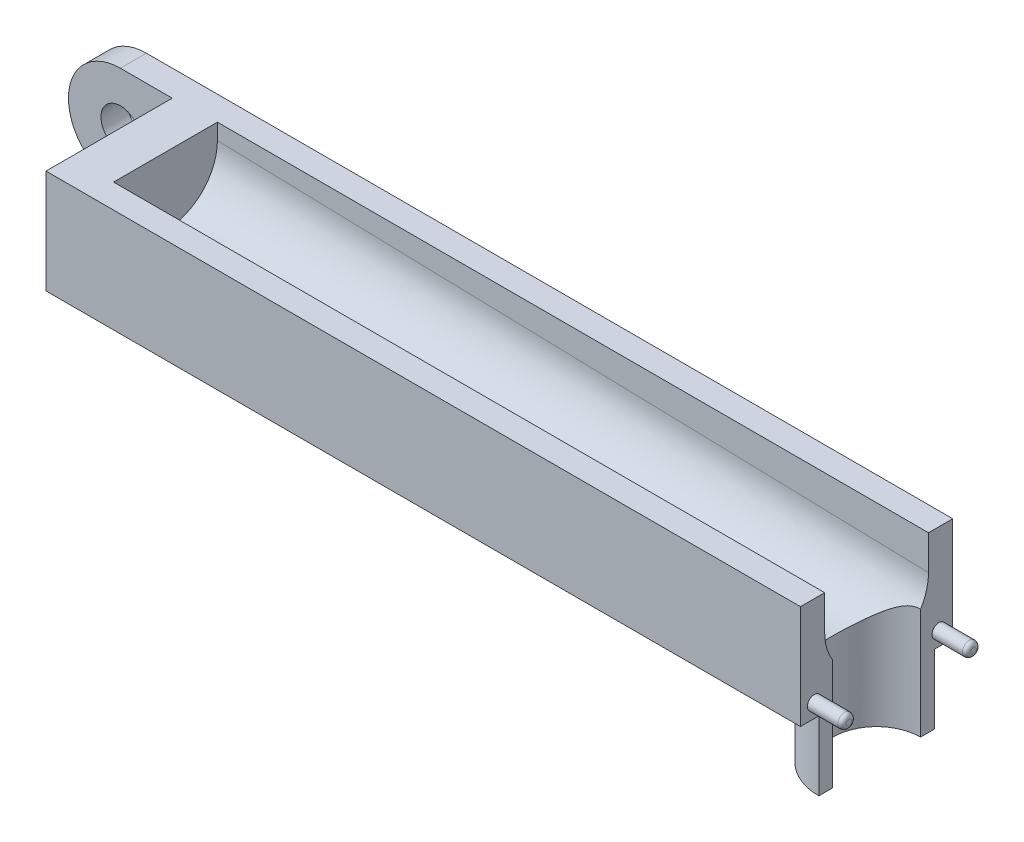
SolidWorks part; units mm, degrees
ref_plane "Front Plane" through (0, 0, 0) normal (0, 0, 1) x (1, 0, 0)
ref_plane "Top Plane" through (0, 0, 0) normal (0, 1, 0) x (1, 0, 0)
ref_plane "Right Plane" through (0, 0, 0) normal (1, 0, 0) x (0, 0, -1)
sketch "Sketch1" plane through (0, 0, 0) normal (1, 0, 0) x (0, 0, -1)
  line L1 (-13.97, -9.525) -> (13.97, -9.525)
  line L2 (-13.97, -9.525) -> (-13.97, 9.525)
  line L3 (-13.97, 9.525) -> (13.97, 9.525)
  line L4 (13.97, -9.525) -> (13.97, 9.525)
  line L5 (-13.97, -9.525) -> (13.97, 9.525) construction
  line L6 (-13.97, 9.525) -> (13.97, -9.525) construction
  point P0 (0, 0)
  dimension "D1" = 27.94
  dimension "D2" = 19.05
extrude "Boss-Extrude1" add sketch "Sketch1" along normal blind 138.4173
sketch "Sketch2" plane through (138.4173, 0, 0) normal (1, 0, 0) x (0, 0, -1)
  line L1 (-13.97, 9.525) -> (-13.97, -9.525) construction
  line L2 (-13.97, -9.525) -> (13.97, -9.525) construction
  line L3 (-9.525, 3.175) -> (-9.525, 9.525)
  line L4 (13.97, 9.525) -> (-13.97, 9.525) construction
  line L5 (-9.525, 9.525) -> (9.525, 9.525)
  line L6 (9.525, 9.525) -> (9.525, 3.175)
  arc A0 (-9.525, 3.175) -> (9.525, 3.175) centre (0, 3.175) ccw
  dimension "D1" = 19.05
  dimension "D2" = 13.97
  dimension "D3" = 12.7
ref_plane "Plane1" through (0, 0, 0) normal (0, 0, 1) x (1, 0, 0)
sketch "Sketch3" plane through (0, 0, 0) normal (0, 0, 1) x (1, 0, 0)
  line L0 (138.4173, 9.525) -> (7.9502, 12.9414)
  line L1 (7.9502, 12.9414) -> (7.9502, 9.525) construction
  line L2 (138.4173, 9.525) -> (0, 9.525) construction
  line L3 (7.9502, 9.525) -> (138.4173, 9.525) construction
  line L4 (0, 9.525) -> (0, -9.525) construction
  dimension "D1" = 7.9502
  dimension "D2" = 1.5
sweep "Cut-Sweep1" cut profiles "Sketch2" path "Sketch3"
sketch "Sketch5" plane through (0, 0, -13.97) normal (0, 0, -1) x (-1, 0, 0)
  line L0 (0, -9.525) -> (0, 9.525) construction
  line L1 (-138.4173, -9.525) -> (0, -9.525) construction
  line L2 (0, -9.525) -> (0, 9.525)
  line L3 (0, 9.525) -> (9.525, 9.525)
  line L4 (9.525, -9.525) -> (0, -9.525)
  arc A0 (9.525, -9.525) -> (9.525, 9.525) centre (9.525, 0) ccw
  circle A1 centre (9.525, 0) radius 3.556
  dimension "D3" = 19.05
  dimension "D4" = 7.112
  dimension "D1" = 9.525
  dimension "D2" = 9.525
extrude "Boss-Extrude2" add sketch "Sketch5" against normal blind 4.7752
sketch "Sketch6" plane through (0, -9.525, 0) normal (0, -1, 0) x (1, 0, 0)
  line L0 (138.4173, 13.97) -> (138.4173, -13.97) construction
  circle A0 centre (138.4173, 0) radius 10.6045
  circle A1 centre (138.4173, 0) radius 8.0645
  dimension "D1" = 21.209
  dimension "D2" = 2.54
extrude "Boss-Extrude3" add sketch "Sketch6" along normal blind 12.7
sketch "Sketch8" plane through (0, -9.525, 0) normal (0, -1, 0) x (1, 0, 0)
  circle A0 centre (138.4173, 0) radius 8.0645 construction
  circle A1 centre (138.4173, 0) radius 8.0645
extrude "Cut-Extrude2" cut sketch "Sketch8" against normal through all
sketch "Sketch9" plane through (0, -9.525, 0) normal (0, -1, 0) x (1, 0, 0)
  line L1 (138.4173, 13.97) -> (171.1347, 13.97)
  line L2 (138.4173, 13.97) -> (138.4173, -10.795)
  line L3 (138.4173, -10.795) -> (171.1347, -10.795)
  line L4 (171.1347, 13.97) -> (171.1347, -10.795)
extrude "Cut-Extrude3" cut sketch "Sketch9" along normal through all
sketch "Sketch10" plane through (138.4173, 0, 0) normal (1, 0, 0) x (0, 0, -1)
  line L0 (-13.97, -9.525) -> (-10.6045, -9.525) construction
  line L1 (-13.97, 9.525) -> (-13.97, -9.525) construction
  line L2 (0, 10.4775) -> (0, -10.4775) construction
  circle A0 centre (-11.43, -6.985) radius 1.27
  circle A1 centre (11.43, -6.985) radius 1.27
  dimension "D3" = 2.54
  dimension "D1" = 2.54
  dimension "D2" = 2.54
extrude "Boss-Extrude4" add sketch "Sketch10" along normal blind 6.35
fillet "Fillet1" radius 0.762 2 edges at (144.7673, -6.985, -10.16) (144.7673, -6.985, 10.16)
